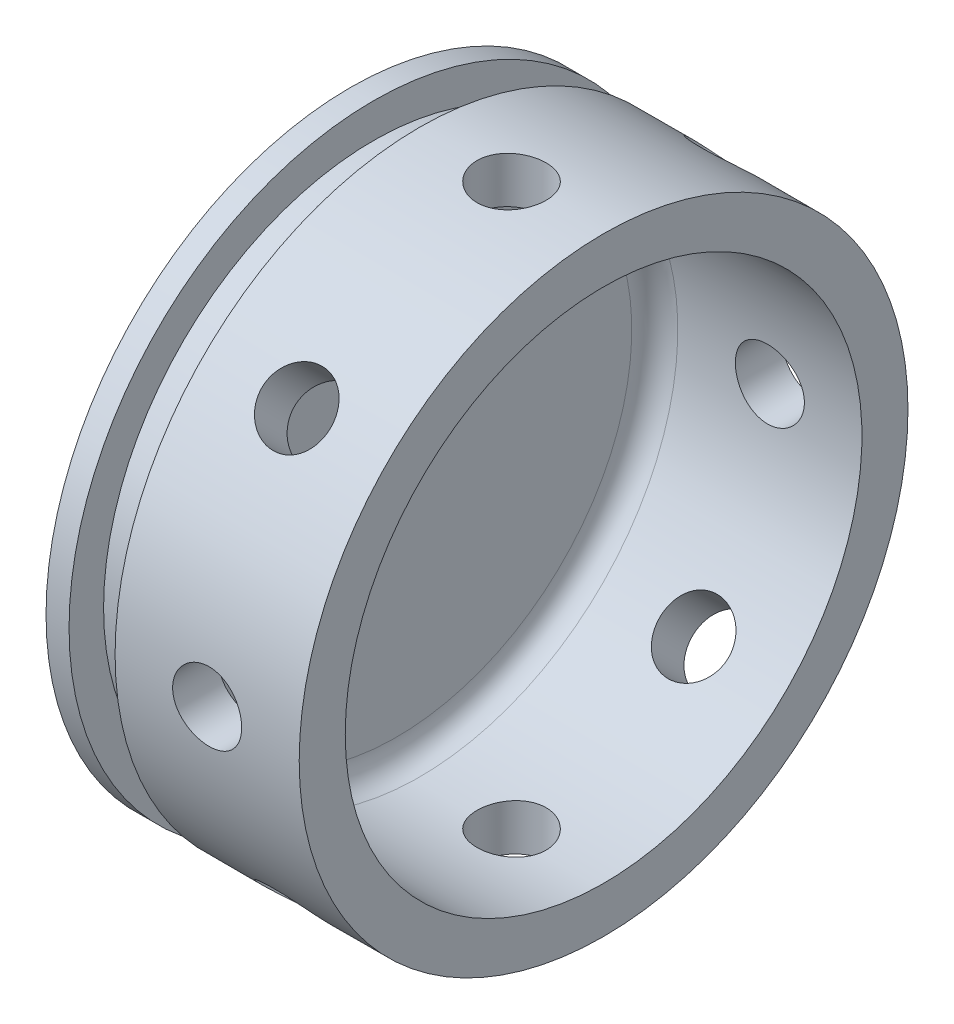
SolidWorks part; units mm, degrees
ref_plane "Front" through (0, 0, 0) normal (0, 0, 1) x (1, 0, 0)
ref_plane "Top" through (0, 0, 0) normal (0, 1, 0) x (1, 0, 0)
ref_plane "Right" through (0, 0, 0) normal (1, 0, 0) x (0, 0, -1)
sketch "Sketch1" plane through (0, 0, 0) normal (0, 1, 0) x (1, 0, 0)
  line L0 (0, 0) -> (43.6365, 0) construction
  line L1 (0, 0) -> (0, 26.45)
  line L2 (22, 26.45) -> (22, 22.45)
  line L3 (22, 22.45) -> (4, 22.45)
  line L4 (4, 22.45) -> (4, 0)
  line L5 (4, 0) -> (0, 0)
  line L6 (0, 26.45) -> (2, 26.45)
  line L7 (2, 26.45) -> (2, 23.45)
  line L8 (2, 23.45) -> (6, 23.45)
  line L9 (6, 23.45) -> (6, 26.45)
  line L10 (6, 26.45) -> (22, 26.45)
  line L11 (22, 26.5) -> (0, 26.5) construction
  dimension "D2" = 4
  dimension "D3" = 4
  dimension "Shoulder" = 22
  dimension "D5" = 2
  dimension "D6" = 4
  dimension "D7" = 3
  dimension "ID" = 26.5
  dimension "Clearance" = 0.05
revolve "Revolve1" add sketch "Sketch1" angle 360 about L0
sketch "Sketch2" plane through (0, 0, 0) normal (0, 1, 0) x (1, 0, 0)
  line L0 (6, 0) -> (22, 0) construction
  line L1 (6, 23.45) -> (6, -23.45) construction
  line L2 (22, -26.45) -> (22, 26.45) construction
  circle A0 centre (14, 0) radius 3
  dimension "Diameter" = 6
extrude "Cut-Extrude1" cut sketch "Sketch2" against normal blind 100
ref_axis "Axis1" through (4, 0, 0) along (1, 0, 0)
pattern_circular "CirPattern1" count 8 over 360 about axis through (4, 0, 0) along (1, 0, 0) of "Cut-Extrude1"
fillet "Fillet1" radius 2 1 edges at (4, 0, 22.45)
